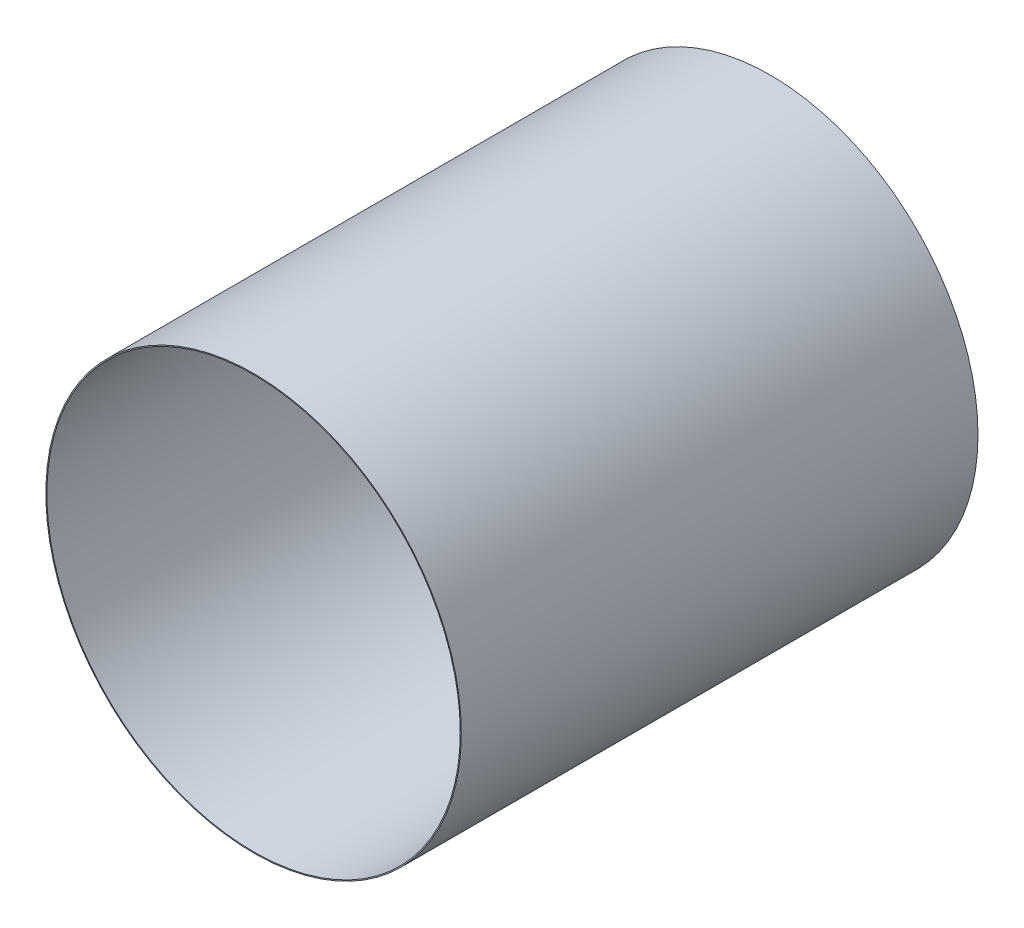
SolidWorks part; units mm, degrees
ref_plane "Front Plane" through (0, 0, 0) normal (0, 0, 1) x (1, 0, 0)
ref_plane "Top Plane" through (0, 0, 0) normal (0, 1, 0) x (1, 0, 0)
ref_plane "Right Plane" through (0, 0, 0) normal (1, 0, 0) x (0, 0, -1)
sketch "Sketch1" plane through (0, 0, 0) normal (0, 0, 1) x (1, 0, 0)
  circle A0 centre (0, 0) radius 10.05
  circle A1 centre (0, 0) radius 10
  dimension "D1" = 20
  dimension "D2" = 20.1
extrude "Boss-Extrude1" add sketch "Sketch1" along normal blind 25
